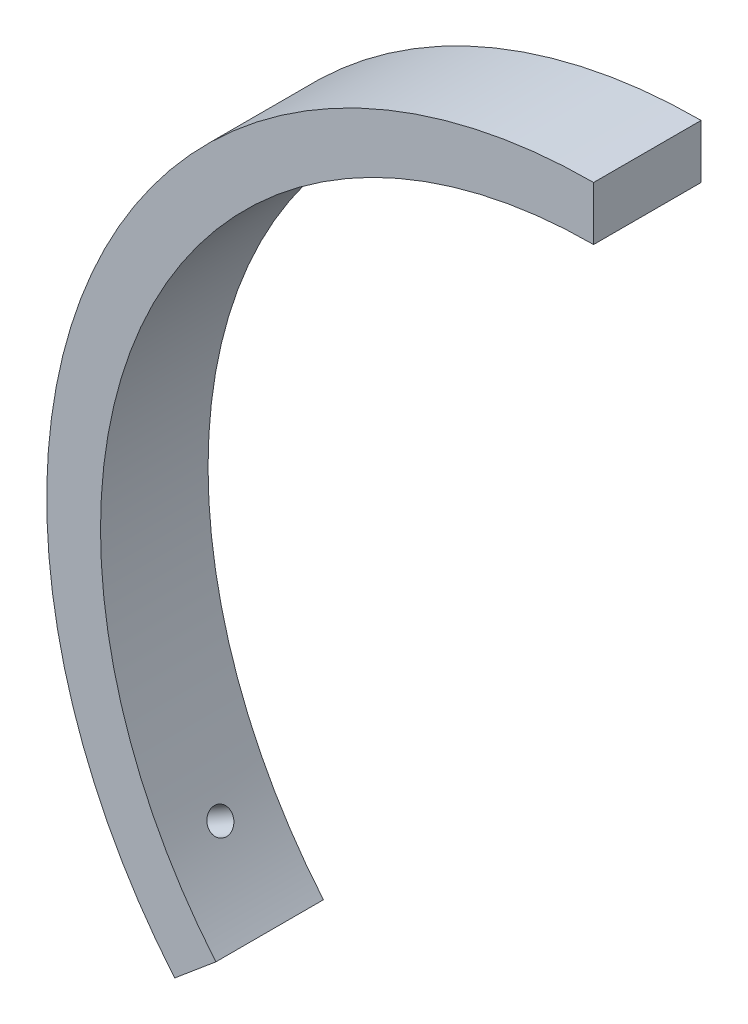
SolidWorks part; units mm, degrees
ref_plane "Piano frontale" through (0, 0, 0) normal (0, 0, 1) x (1, 0, 0)
ref_plane "Piano superiore" through (0, 0, 0) normal (0, 1, 0) x (1, 0, 0)
ref_plane "Piano destro" through (0, 0, 0) normal (1, 0, 0) x (0, 0, -1)
sketch "Schizzo1" plane through (0, 0, 0) normal (0, 0, 1) x (1, 0, 0)
  line L1 (0, 0) -> (-77.9067, -65.3715)
  line L4 (0, 0) -> (-99.5929, -57.5) construction
  line L5 (0, 0) -> (0, 101.7)
  arc A2 (0, 91.7) -> (-70.2463, -58.9436) centre (0, 0) ccw
  arc A3 (0, 101.7) -> (-77.9067, -65.3715) centre (0, 0) ccw
  dimension "D2" = 91.7
  dimension "D3" = 10
  dimension "D1" = 230
  dimension "D4" = 10
extrude "Estrusione-Estrusione1" add sketch "Schizzo1" along normal blind 20 contours L4 A2 L5 A3 | A2 L4 A3 L1
hole_wizard "Foro svasato per Vite M4-1" positions "Schizzo3D1" profile "Schizzo3" countersink size "M4" standard "Ansi Metric"
sketch3d "Schizzo3D1"
  line L0 (-88.0748, -50.85, 0) -> (-88.0748, -50.85, 9.1126) construction
  line L2 (0, 0, 0) -> (-99.5929, -57.5, 0) construction
  point P0 (-88.0748, -50.85, 10)
  point P11 (-100.3409, -56.2044, 9.784)
  point P12 (-98.6639, -59.1091, 8.5677)
  point P13 (0, 0, 0)
  point P14 (0, 0, 0)
  point P15 (-95.8698, -55.3505, 0)
  dimension "D1" = 10
sketch "Schizzo3" plane through (-88.0748, -50.85, 10) normal (0, 0, 1) x (0.5, -0.866, 0)
  line L0 (0, 0) -> (0, 31.3519)
  line L1 (0, 31.3519) -> (2.25, 30)
  line L2 (2.25, 30) -> (2.25, 2.45)
  line L3 (2.25, 2.45) -> (4.7, 0)
  line L5 (4.7, 0) -> (0, 0)
  line L6 (-2.25, 2.45) -> (-4.7, 0) construction
  line L10 (0, 31.3519) -> (-2.25, 30) construction
  line L11 (0, -6.35) -> (0, 107.95) construction
  dimension "Hole Dia." = 4.5
  dimension "Hole Depth" = 30
  dimension "Near C'Sink Dia." = 9.4
  dimension "Near C'Sink Angle" = 90
  dimension "Drill Angle" = 118
